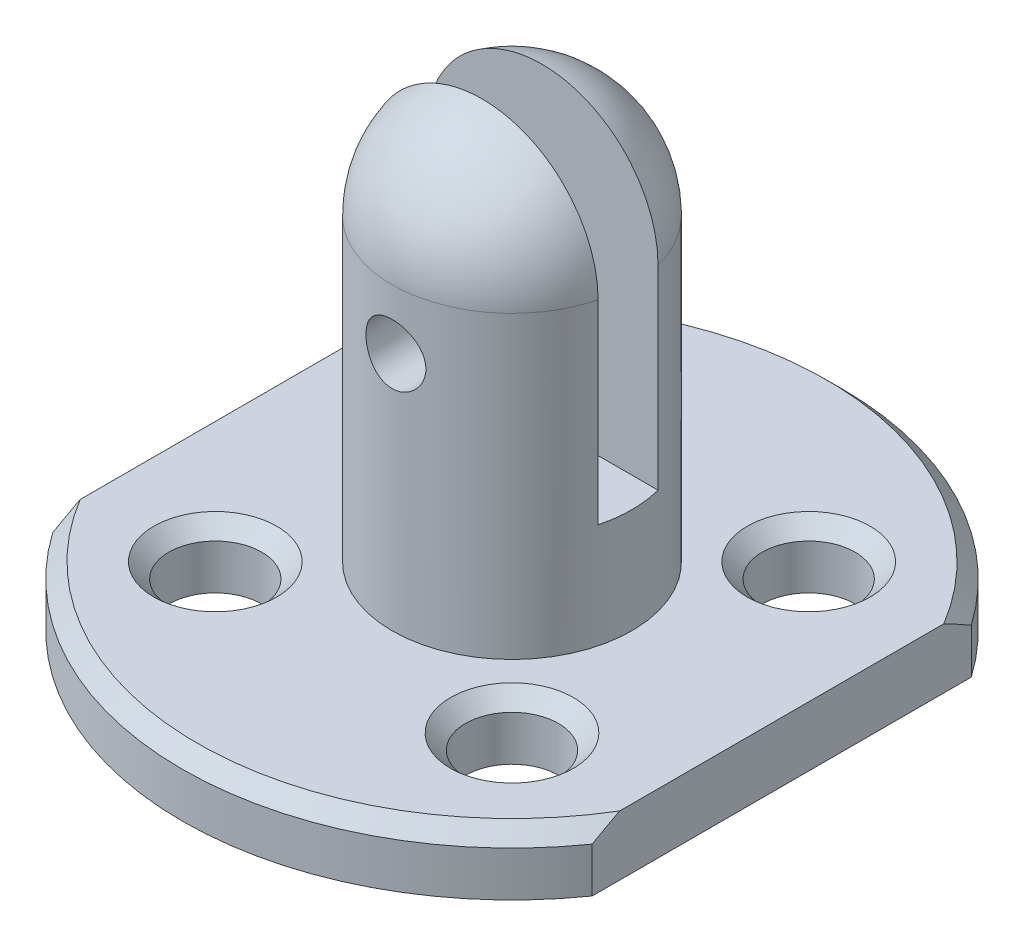
SolidWorks part; units mm, degrees
ref_plane "Front Plane" through (0, 0, 0) normal (0, 0, 1) x (1, 0, 0)
ref_plane "Top Plane" through (0, 0, 0) normal (0, 1, 0) x (1, 0, 0)
ref_plane "Right Plane" through (0, 0, 0) normal (1, 0, 0) x (0, 0, -1)
sketch "Sketch1" plane through (0, 0, 0) normal (0, 1, 0) x (1, 0, 0)
  line L2 (9, -6.3246) -> (9, 6.3246)
  line L4 (-9, -6.3246) -> (-9, 6.3246)
  line L5 (9, -12.2159) -> (-9, 12.2159) construction
  line L6 (9, 12.2159) -> (-9, -12.2159) construction
  arc A0 (-9, -6.3246) -> (9, -6.3246) centre (0, 0) ccw
  arc A1 (9, 6.3246) -> (-9, 6.3246) centre (0, 0) ccw
  dimension "D1" = 22
  dimension "D2" = 18
extrude "Boss-Extrude1" add sketch "Sketch1" along normal blind 2
sketch "Sketch2" plane through (0, 2, 0) normal (0, 1, 0) x (1, 0, 0)
  line L0 (0, 0) -> (0, 7) construction
  line L1 (0, 0) -> (4.9497, 4.9497) construction
  circle A0 centre (0, 0) radius 7 construction
  circle A1 centre (4.9497, 4.9497) radius 1.55
  circle A2 centre (4.9497, -4.9497) radius 1.55
  circle A3 centre (-4.9497, -4.9497) radius 1.55
  circle A4 centre (-4.9497, 4.9497) radius 1.55
  point P15 (0, 0)
  dimension "D1" = 14
  dimension "D3" = 3.1
  dimension "D2" = 45
  dimension "D4" = 4
extrude "Cut-Extrude1" cut sketch "Sketch2" against normal through all
chamfer "Chamfer1" distance 0.5 angle 45 6 edges at (0, 2, -11) (-4.9497, 2, 6.4997) (-4.9497, 2, -3.3997) (4.9497, 2, -3.3997) (4.9497, 2, 6.4997) (0, 2, 11)
sketch "Sketch3" plane through (0, 0, 0) normal (0, 0, 1) x (1, 0, 0)
  line L0 (0, 2) -> (0, 16)
  line L1 (9, 2) -> (-9, 2) construction
  line L2 (4, 12) -> (4, 2)
  line L3 (4, 2) -> (0, 2)
  arc A1 (0, 16) -> (4, 12) centre (0, 12) cw
  dimension "D1" = 14
  dimension "D2" = 4
  dimension "D3" = 10
revolve "Revolve1" add sketch "Sketch3" angle 360 about L0
sketch "Sketch4" plane through (0, 0, 0) normal (1, 0, 0) x (0, 0, -1)
  line L0 (-5.4083, 2) -> (5.4083, 2) construction
  line L1 (-1, 5.5) -> (1, 5.5)
  line L2 (-1, 5.5) -> (-1, 19.4638)
  line L3 (-1, 19.4638) -> (1, 19.4638)
  line L4 (1, 5.5) -> (1, 19.4638)
  line L5 (-1, 5.5) -> (1, 19.4638) construction
  line L6 (-1, 19.4638) -> (1, 5.5) construction
  point P0 (0, 12.4819)
  dimension "D1" = 3.5
  dimension "D2" = 2
extrude "Cut-Extrude2" cut sketch "Sketch4" against normal through all both and the other way through all
sketch "Sketch5" plane through (0, 0, 0) normal (0, 0, 1) x (1, 0, 0)
  line L0 (9, 2) -> (-9, 2) construction
  circle A0 centre (0, 10) radius 1
  dimension "D1" = 2
  dimension "D2" = 8
extrude "Cut-Extrude3" cut sketch "Sketch5" against normal through all both and the other way through all
sketch "Sketch6" plane through (0, 0, 0) normal (0, -1, 0) x (1, 0, 0)
  circle A0 centre (0, 0) radius 3
  dimension "D1" = 6
extrude "Boss-Extrude2" add sketch "Sketch6" along normal blind 1
